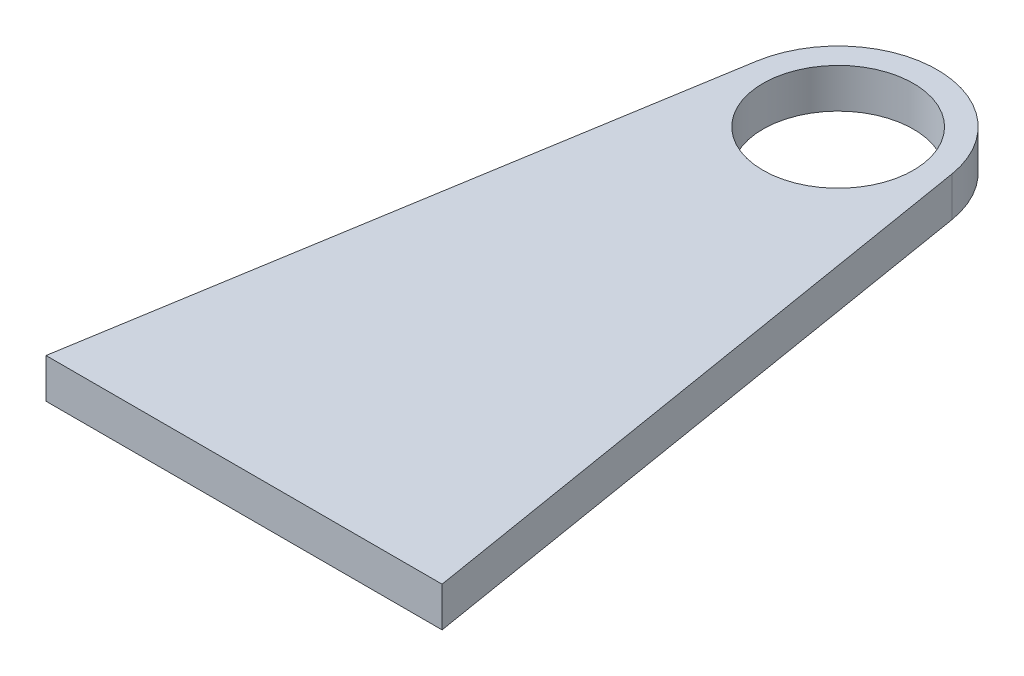
SolidWorks part; units mm, degrees
ref_plane "Front Plane" through (0, 0, 0) normal (0, 0, 1) x (1, 0, 0)
ref_plane "Top Plane" through (0, 0, 0) normal (0, 1, 0) x (1, 0, 0)
ref_plane "Right Plane" through (0, 0, 0) normal (1, 0, 0) x (0, 0, -1)
sketch "Sketch1" plane through (0, 0, 0) normal (0, 1, 0) x (1, 0, 0)
  line L0 (-25, -75) -> (25, -75)
  line L1 (-25, -75) -> (-12.3344, 2.0281)
  line L2 (25, -75) -> (12.3344, 2.0281)
  circle A0 centre (0, 0) radius 9.5
  arc A1 (12.3344, 2.0281) -> (-12.3344, 2.0281) centre (0, 0) ccw
  point P7 (0, -75)
  dimension "D1" = 19
  dimension "D2" = 25
  dimension "D3" = 75
  dimension "D4" = 50
extrude "Boss-Extrude1" add sketch "Sketch1" along normal blind 5
